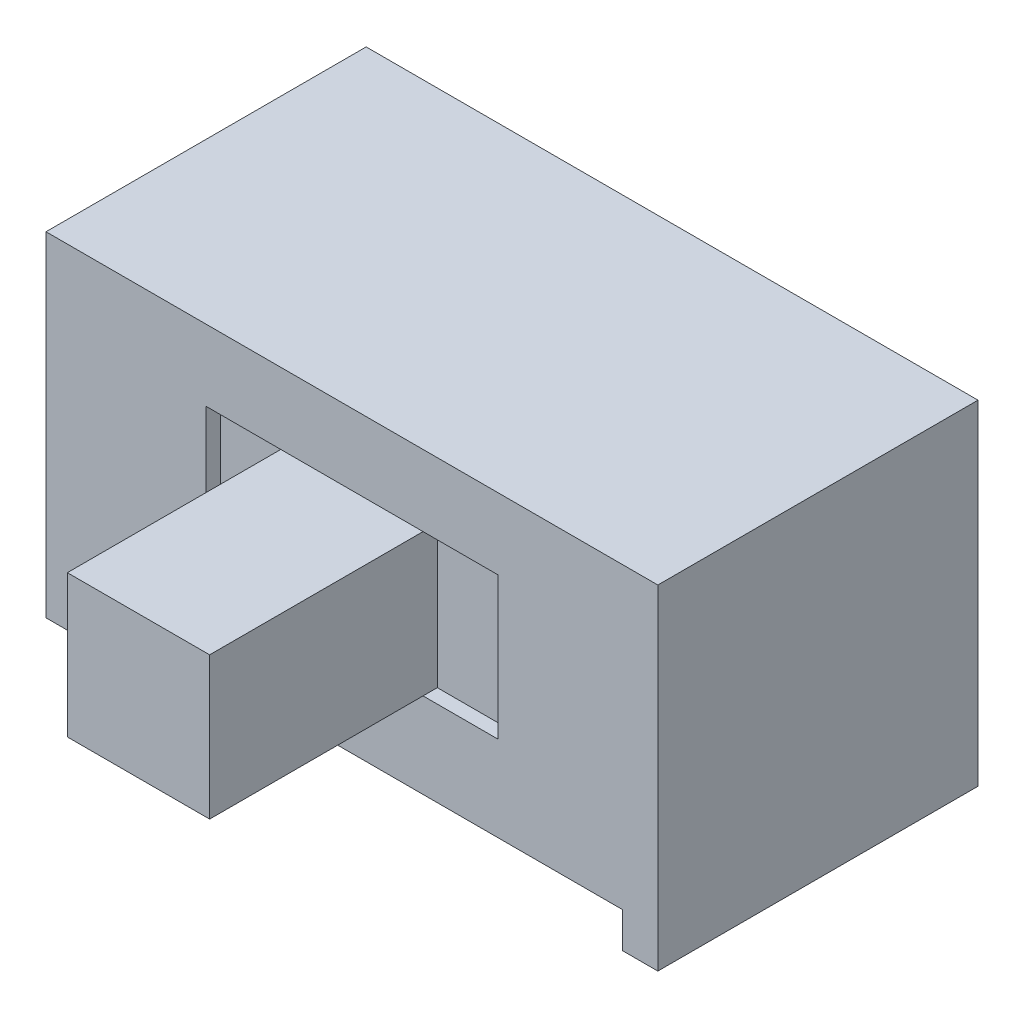
SolidWorks part; units mm, degrees
ref_plane "前视基准面" through (0, 0, 0) normal (0, 0, 1) x (1, 0, 0)
ref_plane "上视基准面" through (0, 0, 0) normal (0, 1, 0) x (1, 0, 0)
ref_plane "右视基准面" through (0, 0, 0) normal (1, 0, 0) x (0, 0, -1)
sketch "草图1" plane through (0, 0, 0) normal (0, 1, 0) x (1, 0, 0)
  line L1 (0, 0) -> (8.6, 0)
  line L2 (0, 0) -> (0, 4.5)
  line L3 (0, 4.5) -> (8.6, 4.5)
  line L4 (8.6, 0) -> (8.6, 4.5)
  dimension "D1" = 8.6
  dimension "D2" = 4.5
extrude "凸台-拉伸1" add sketch "草图1" along normal blind 4.7
sketch "草图2" plane through (0, 0, 0) normal (0, 0, 1) x (1, 0, 0)
  line L0 (4.3, 6.201) -> (4.3, -2.4586) construction
  line L1 (2.25, 3.7) -> (6.35, 3.7)
  line L2 (2.25, 3.7) -> (2.25, 1.7)
  line L3 (2.25, 1.7) -> (6.35, 1.7)
  line L4 (6.35, 3.7) -> (6.35, 1.7)
  line L7 (1.0818, 2.7) -> (7.44, 2.7) construction
  line L9 (0, 0) -> (8.6, 0) construction
  dimension "D1" = 4.1
  dimension "D2" = 2.7
  dimension "D3" = 2
extrude "切除-拉伸1" cut sketch "草图2" against normal blind 0.2
sketch "草图4" plane through (0, 0, 0) normal (0, 0, 1) x (1, 0, 0)
  line L0 (0.5, 0) -> (0.5, 0.5)
  line L1 (0, 0) -> (8.6, 0) construction
  line L2 (0.5, 0.5) -> (8.1, 0.5)
  line L3 (8.1, 0.5) -> (8.1, 0)
  line L4 (8.1, 0) -> (0.5, 0)
  line L6 (8.1, 0) -> (8.6, 0) construction
  line L7 (0.5, 0) -> (0, 0) construction
  dimension "D1" = 0.5
  dimension "D2" = 0.5
extrude "切除-拉伸2" cut sketch "草图4" against normal up to next
sketch "草图5" plane through (0, 0, 0) normal (0, 0, 1) x (1, 0, 0)
  line L0 (6.35, 3.7) -> (2.25, 3.7) construction
  line L1 (4.3, 4.5445) -> (4.3, -0.2014) construction
  line L2 (3.3, 3.7) -> (5.3, 3.7)
  line L3 (3.3, 3.7) -> (3.3, 1.7)
  line L4 (3.3, 1.7) -> (5.3, 1.7)
  line L5 (5.3, 3.7) -> (5.3, 1.7)
  line L6 (2.25, 1.7) -> (6.35, 1.7) construction
  dimension "D1" = 2
extrude "凸台-拉伸2" add sketch "草图5" along normal blind 3 and the other way up to surface other way up to face at (4.3, 2.7, -0.2)
